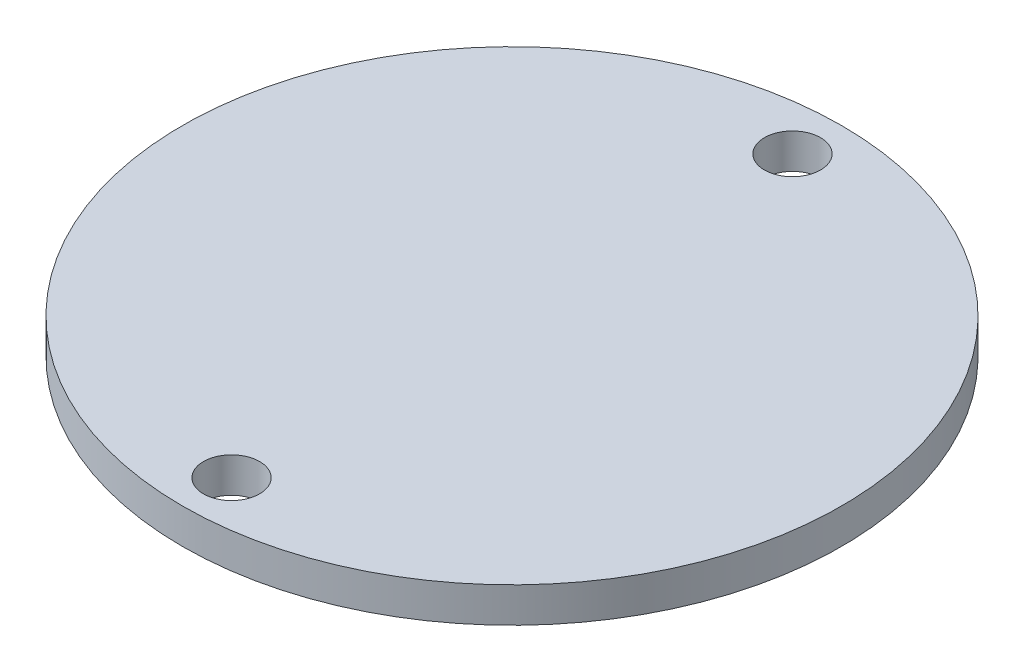
SolidWorks part; units mm, degrees
ref_plane "Plano frontal" through (0, 0, 0) normal (0, 0, 1) x (1, 0, 0)
ref_plane "Plano superior" through (0, 0, 0) normal (0, 1, 0) x (1, 0, 0)
ref_plane "Plano direito" through (0, 0, 0) normal (1, 0, 0) x (0, 0, -1)
sketch "Esboço1" plane through (0, 0, 0) normal (0, 1, 0) x (1, 0, 0)
  line L0 (-37.6448, 0) -> (49.3018, 0) construction
  line L1 (0, 27.534) -> (0, -28.6377) construction
  circle A0 centre (0, 0) radius 23.5
  circle A1 centre (0, -20) radius 2
  circle A3 centre (0, 20) radius 2
  dimension "D1" = 47
  dimension "D3" = 20
  dimension "D4" = 4
  dimension "D5" = 4
  dimension "D2" = 20
extrude "Ressalto-extrusão1" add sketch "Esboço1" along normal blind 2.5
